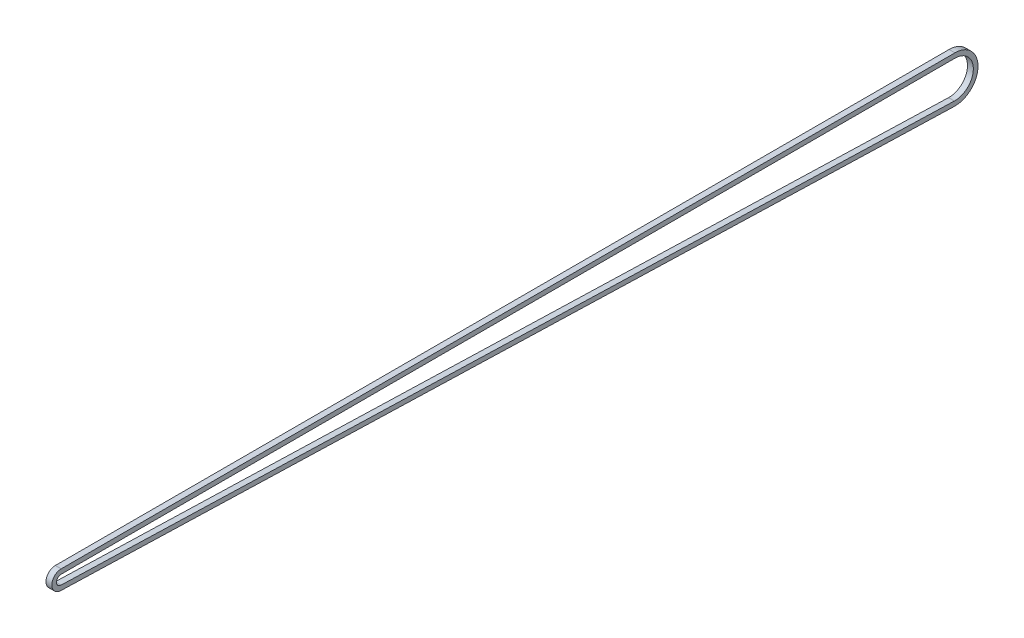
SolidWorks part; units mm, degrees
material "ｺﾞﾑ"
ref_plane "正面" through (0, 0, 0) normal (0, 0, 1) x (1, 0, 0)
ref_plane "平面" through (0, 0, 0) normal (0, 1, 0) x (1, 0, 0)
ref_plane "右側面" through (0, 0, 0) normal (1, 0, 0) x (0, 0, -1)
sketch "ｽｹｯﾁ1" plane through (0, 0, 0) normal (1, 0, 0) x (0, 0, -1)
  line L0 (0, 0) -> (765.52, -11.75) construction
  line L1 (0, 8) -> (765.52, 8)
  line L2 (-0.2455, -7.9962) -> (764.9139, -31.4907)
  line L3 (0, 4) -> (765.52, 4)
  line L4 (765.0366, -27.4926) -> (-0.1228, -3.9981)
  arc A0 (0, 8) -> (-0.2455, -7.9962) centre (0, 0) ccw
  arc A1 (764.9139, -31.4907) -> (765.52, 8) centre (765.52, -11.75) ccw
  arc A2 (7.9991, -0.1228) -> (0, 8) centre (0, 0) ccw construction
  arc A3 (-0.2455, -7.9962) -> (7.9991, -0.1228) centre (0, 0) ccw construction
  arc A4 (745.7723, -11.4469) -> (764.9139, -31.4907) centre (765.52, -11.75) ccw construction
  arc A5 (765.52, 8) -> (745.7723, -11.4469) centre (765.52, -11.75) ccw construction
  circle A6 centre (765.52, -11.75) radius 15.75
  circle A7 centre (0, 0) radius 4
  dimension "D1" = 16
  dimension "D2" = 39.5
  dimension "D4" = 31.5
  dimension "D3" = 765.52
extrude "ﾎﾞｽ - 押し出し1" add sketch "ｽｹｯﾁ1" along normal blind 5 contours L2 A1 L1 A0 A7 L3 A6 L4
